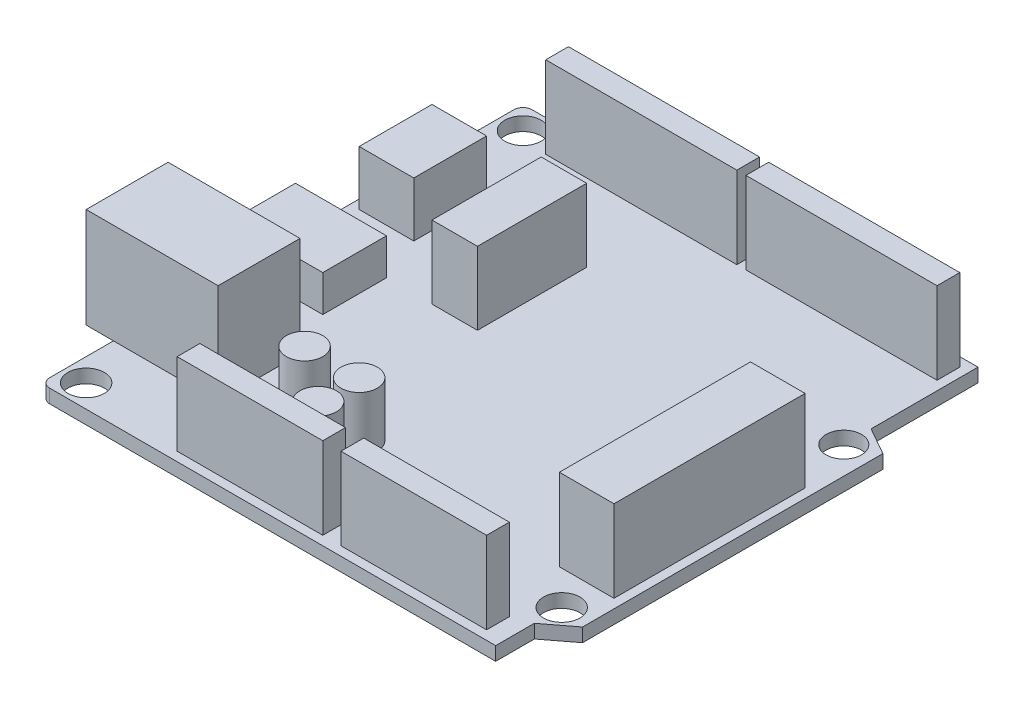
SolidWorks part; units mm, degrees
ref_plane "Front Plane" through (0, 0, 0) normal (0, 0, 1) x (1, 0, 0)
ref_plane "Top Plane" through (0, 0, 0) normal (0, 1, 0) x (1, 0, 0)
ref_plane "Right Plane" through (0, 0, 0) normal (1, 0, 0) x (0, 0, -1)
sketch "Sketch1" plane through (0, 0, 0) normal (0, 1, 0) x (1, 0, 0)
  line L1 (25, -26.5) -> (-25, -26.5)
  line L2 (25, -26.5) -> (25, 26.5)
  line L3 (25, 26.5) -> (-25, 26.5)
  line L4 (-25, -26.5) -> (-25, 26.5)
  line L5 (25, -26.5) -> (-25, 26.5) construction
  line L6 (25, 26.5) -> (-25, -26.5) construction
  point P0 (0, 0)
  dimension "D1" = 53
  dimension "D2" = 50
extrude "Boss-Extrude1" add sketch "Sketch1" along normal mid plane 1.5
sketch "Sketch3" plane through (0, 0.75, 0) normal (0, 1, 0) x (1, 0, 0)
  line L0 (25, -22.2469) -> (25, 14.7531)
  line L1 (25, -26.5) -> (25, 26.5) construction
  line L2 (25, 14.7531) -> (28, 13.047)
  line L3 (28, 13.047) -> (28, -19.953)
  line L4 (28, -19.953) -> (25, -22.2469)
  dimension "D1" = 3
  dimension "D2" = 37
  dimension "D3" = 33
extrude "Boss-Extrude2" add sketch "Sketch3" against normal blind 1.5 separate body
sketch "Sketch7" plane through (0, 0.75, 0) normal (0, 1, 0) x (1, 0, 0)
  line L0 (-25, 26.5) -> (-25, -26.5) construction
  line L1 (25, 26.5) -> (-25, 26.5) construction
  line L2 (25, 14.7531) -> (25, -22.2469) construction
  line L3 (-25, -26.5) -> (25, -26.5) construction
  circle A0 centre (-22.5, 24) radius 2
  circle A1 centre (-22.5, -24) radius 2
  circle A2 centre (25, 11.7531) radius 1.9483
  circle A3 centre (25, -19.2469) radius 2
  dimension "D1" = 2.5
  dimension "D3" = 3
  dimension "D4" = 3
  dimension "D2" = 2.5
  dimension "D5" = 2.5
  dimension "D6" = 2.5
extrude "Cut-Extrude1" cut sketch "Sketch7" against normal through all
sketch "Sketch8" plane through (0, 0.75, 0) normal (0, 1, 0) x (1, 0, 0)
  line L0 (25, 26.5) -> (-25, 26.5) construction
  line L1 (24, 25.5) -> (3, 25.5)
  line L2 (24, 25.5) -> (24, 23)
  line L3 (24, 23) -> (3, 23)
  line L4 (3, 25.5) -> (3, 23)
  line L5 (2, 25.5) -> (-19, 25.5)
  line L6 (2, 25.5) -> (2, 23)
  line L7 (2, 23) -> (-19, 23)
  line L8 (-19, 25.5) -> (-19, 23)
  line L9 (-25, -26.5) -> (25, -26.5) construction
  line L10 (27, -15.5) -> (21, -15.5)
  line L11 (27, -15.5) -> (27, 5.5)
  line L12 (27, 5.5) -> (21, 5.5)
  line L13 (21, -15.5) -> (21, 5.5)
  line L14 (28, -19.953) -> (28, 13.047) construction
  line L15 (25, -26.5) -> (25, -21.2469) construction
  line L16 (23, -23) -> (7, -23)
  line L17 (23, -23) -> (23, -25.5)
  line L18 (23, -25.5) -> (7, -25.5)
  line L19 (7, -23) -> (7, -25.5)
  line L20 (5, -23) -> (-11, -23)
  line L21 (5, -23) -> (5, -25.5)
  line L22 (5, -25.5) -> (-11, -25.5)
  line L23 (-11, -23) -> (-11, -25.5)
  line L24 (25, 13.7014) -> (25, 26.5) construction
  dimension "D1" = 2.5
  dimension "D2" = 2.5
  dimension "D3" = 3.5
  dimension "D4" = 21
  dimension "D5" = 3.5
  dimension "D6" = 21
  dimension "D7" = 6
  dimension "D8" = 21
  dimension "D9" = 32
  dimension "D10" = 1
  dimension "D11" = 16
  dimension "D12" = 16
  dimension "D13" = 2.5
  dimension "D14" = 2.5
  dimension "D15" = 1
  dimension "D16" = 1
  dimension "D17" = 2
  dimension "D18" = 2
  dimension "D19" = 1
  dimension "D20" = 1
extrude "Boss-Extrude3" add sketch "Sketch8" along normal blind 9
sketch "Sketch9" plane through (0, 0.75, 0) normal (0, 1, 0) x (1, 0, 0)
  line L0 (-25, -26.5) -> (25, -26.5) construction
  line L1 (-25, 26.5) -> (-25, -26.5) construction
  circle A0 centre (-2, -19) radius 2
  circle A1 centre (-2, -14.5) radius 2
  circle A2 centre (-8, -14.5) radius 2
  dimension "D1" = 4
  dimension "D2" = 4
  dimension "D3" = 4
  dimension "D4" = 6
  dimension "D5" = 12
  dimension "D6" = 4.5
  dimension "D7" = 23
  dimension "D8" = 23
  dimension "D9" = 12
extrude "Boss-Extrude4" add sketch "Sketch9" along normal blind 6
sketch "Sketch10" plane through (0, 0.75, 0) normal (0, 1, 0) x (1, 0, 0)
  line L0 (-25, -26.5) -> (25, -26.5) construction
  line L1 (-13.5, -18.5) -> (-28, -18.5)
  line L2 (-13.5, -18.5) -> (-13.5, -9.5)
  line L3 (-13.5, -9.5) -> (-28, -9.5)
  line L4 (-28, -18.5) -> (-28, -9.5)
  line L5 (-25, 26.5) -> (-25, -26.5) construction
  dimension "D1" = 8
  dimension "D2" = 14.5
  dimension "D3" = 9
  dimension "D4" = 3
extrude "Boss-Extrude5" add sketch "Sketch10" along normal blind 11
sketch "Sketch11" plane through (0, 0.75, 0) normal (0, 1, 0) x (1, 0, 0)
  line L0 (-13.5, -9.5) -> (-25, -9.5) construction
  line L1 (-16, -4.5) -> (-26, -4.5)
  line L2 (-16, -4.5) -> (-16, 2.5)
  line L3 (-16, 2.5) -> (-26, 2.5)
  line L4 (-26, -4.5) -> (-26, 2.5)
  line L5 (-25, 26.5) -> (-25, -26.5) construction
  point P6 (-25, 0)
  dimension "D1" = 5
  dimension "D2" = 10
  dimension "D3" = 7
  dimension "D4" = 1
extrude "Boss-Extrude6" add sketch "Sketch11" along normal blind 4
sketch "Sketch12" plane through (0, 0.75, 0) normal (0, 1, 0) x (1, 0, 0)
  line L0 (-16, 2.5) -> (-25, 2.5) construction
  line L1 (-18, 7.5) -> (-24, 7.5)
  line L2 (-18, 7.5) -> (-18, 15.5)
  line L3 (-18, 15.5) -> (-24, 15.5)
  line L4 (-24, 7.5) -> (-24, 15.5)
  line L5 (-25, 26.5) -> (-25, 2.5) construction
  dimension "D1" = 8
  dimension "D2" = 6
  dimension "D3" = 5
  dimension "D4" = 1
extrude "Boss-Extrude7" add sketch "Sketch12" along normal blind 6
sketch "Sketch13" plane through (0, 0.75, 0) normal (0, 1, 0) x (1, 0, 0)
  line L0 (-25, 26.5) -> (-25, 2.5) construction
  line L1 (-11, 2.5) -> (-6, 2.5)
  line L2 (-11, 2.5) -> (-11, 14.5)
  line L3 (-11, 14.5) -> (-6, 14.5)
  line L4 (-6, 2.5) -> (-6, 14.5)
  line L5 (25, 26.5) -> (-25, 26.5) construction
  dimension "D1" = 12
  dimension "D2" = 5
  dimension "D3" = 19
  dimension "D4" = 24
extrude "Boss-Extrude8" add sketch "Sketch13" along normal blind 8
fillet "Fillet4" radius 1 1 edges at (-25, 0, -26.5)
fillet "Fillet5" radius 1 1 edges at (-25, 0, 26.5)
